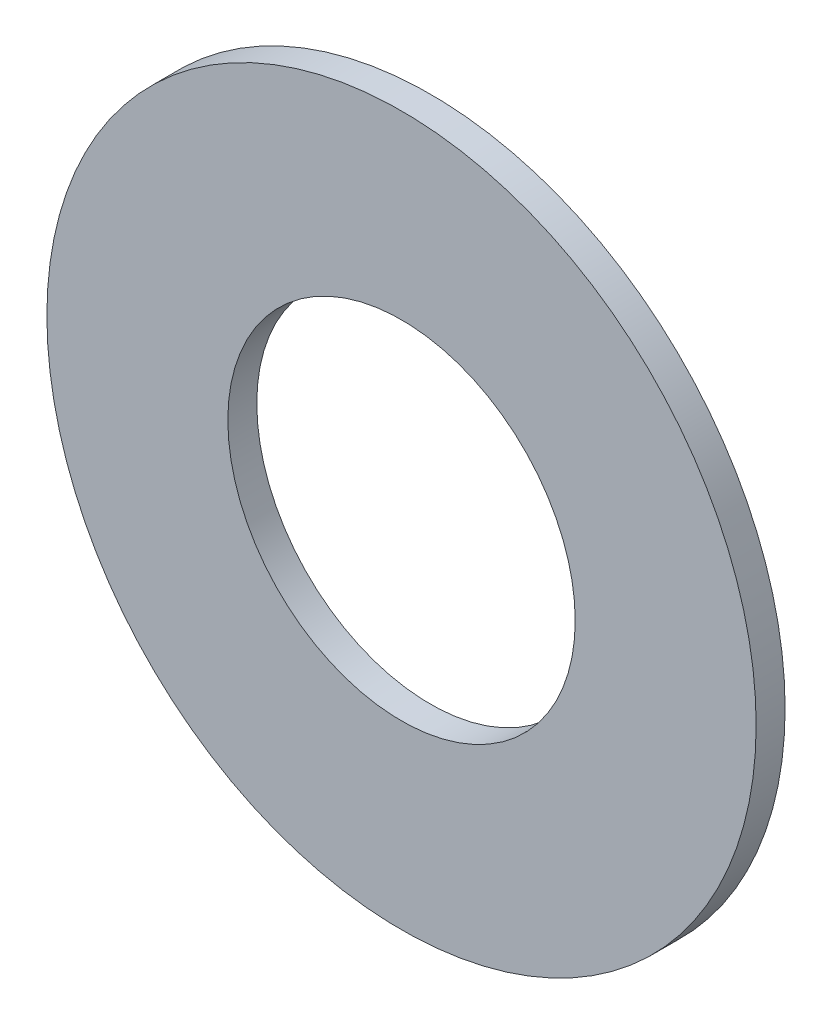
SolidWorks part; units mm, degrees
ref_plane "前视基准面" through (0, 0, 0) normal (0, 0, 1) x (1, 0, 0)
ref_plane "上视基准面" through (0, 0, 0) normal (0, 1, 0) x (1, 0, 0)
ref_plane "右视基准面" through (0, 0, 0) normal (1, 0, 0) x (0, 0, -1)
other "Configuration Table"
sketch "草图2" plane through (0, 0, 0) normal (0, 0, 1) x (1, 0, 0)
  circle A0 centre (0, 0) radius 12.25
  circle A1 centre (0, 0) radius 6
  dimension "D1" = 24.5
  dimension "D2" = 12
extrude "凸台-拉伸1" add sketch "草图2" along normal blind 1
